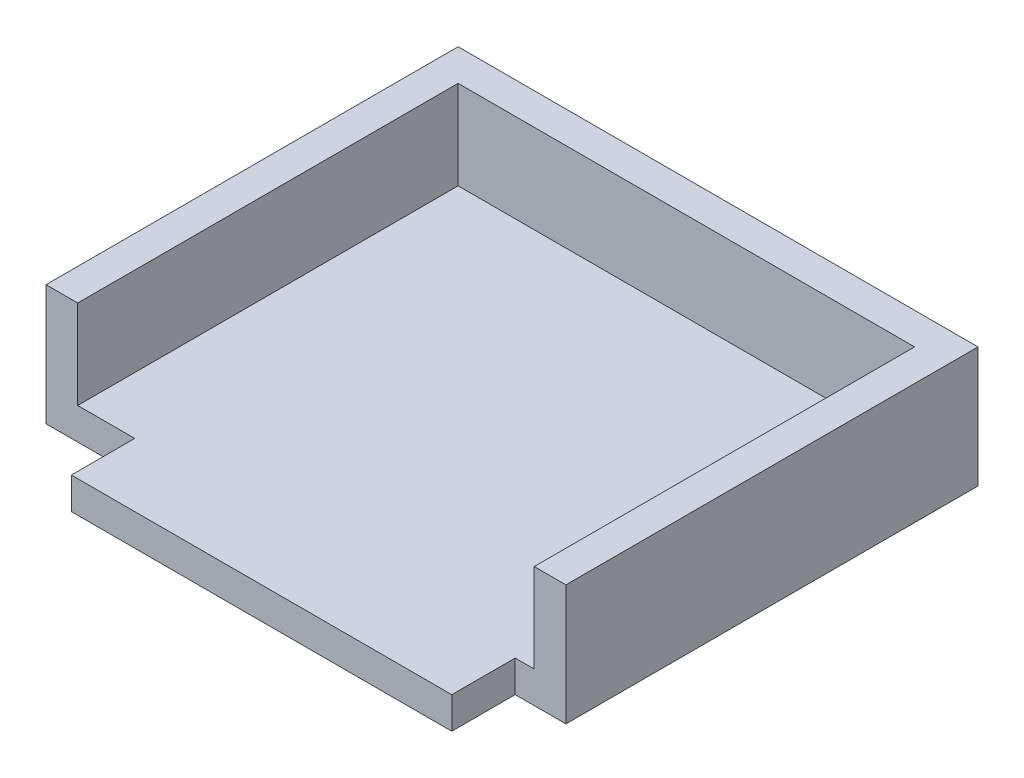
SolidWorks part; units mm, degrees
ref_plane "Plan de face" through (0, 0, 0) normal (0, 0, 1) x (1, 0, 0)
ref_plane "Plan de dessus" through (0, 0, 0) normal (0, 1, 0) x (1, 0, 0)
ref_plane "Plan de droite" through (0, 0, 0) normal (1, 0, 0) x (0, 0, -1)
sketch "Esquisse1" plane through (0, 0, 0) normal (0, 1, 0) x (1, 0, 0)
  line L0 (-69.1915, -43.1682) -> (-55.1915, -43.1682)
  line L1 (-69.1915, 21.8318) -> (12.8085, 21.8318)
  line L2 (-69.1915, 21.8318) -> (-69.1915, -43.1682)
  line L3 (-55.1915, -43.1682) -> (-55.1915, -53.1682)
  line L4 (12.8085, 21.8318) -> (12.8085, -43.1682)
  line L5 (-55.1915, -53.1682) -> (4.8085, -53.1682)
  line L6 (4.8085, -53.1682) -> (4.8085, -43.1682)
  line L7 (4.8085, -43.1682) -> (12.8085, -43.1682)
  dimension "D1" = 82
  dimension "D2" = 65
  dimension "D3" = 10
  dimension "D4" = 14
  dimension "D5" = 60
extrude "Extrusion1" add sketch "Esquisse1" along normal blind 5
sketch "Esquisse2" plane through (0, 5, 0) normal (0, 1, 0) x (1, 0, 0)
  line L0 (12.8085, -43.1682) -> (12.8085, 21.8318)
  line L1 (12.8085, 21.8318) -> (-69.1915, 21.8318)
  line L2 (-69.1915, 21.8318) -> (-69.1915, -43.1682)
  line L3 (-69.1915, -43.1682) -> (-64.1915, -43.1682)
  line L4 (7.8085, -43.1682) -> (12.8085, -43.1682)
  line L8 (-69.1915, -43.1682) -> (-55.1915, -43.1682) construction
  line L11 (4.8085, -43.1682) -> (12.8085, -43.1682) construction
  line L16 (-64.1915, 16.8318) -> (-64.1915, -38.1682)
  line L17 (-64.1915, -38.1682) -> (-50.1915, -38.1682)
  line L18 (-50.1915, -38.1682) -> (-50.1915, -48.1682)
  line L19 (-50.1915, -48.1682) -> (-0.1915, -48.1682)
  line L20 (-0.1915, -48.1682) -> (-0.1915, -38.1682)
  line L21 (-0.1915, -38.1682) -> (7.8085, -38.1682)
  line L22 (7.8085, -38.1682) -> (7.8085, 16.8318)
  line L23 (7.8085, 16.8318) -> (-64.1915, 16.8318)
  line L24 (-64.1915, 16.8318) -> (-64.1915, -43.1682)
  line L30 (7.8085, -43.1682) -> (7.8085, 16.8318)
  line L31 (7.8085, 16.8318) -> (-64.1915, 16.8318)
  dimension "D1" = 5
  dimension "D2" = 5
extrude "Extrusion2" add sketch "Esquisse2" along normal blind 14
